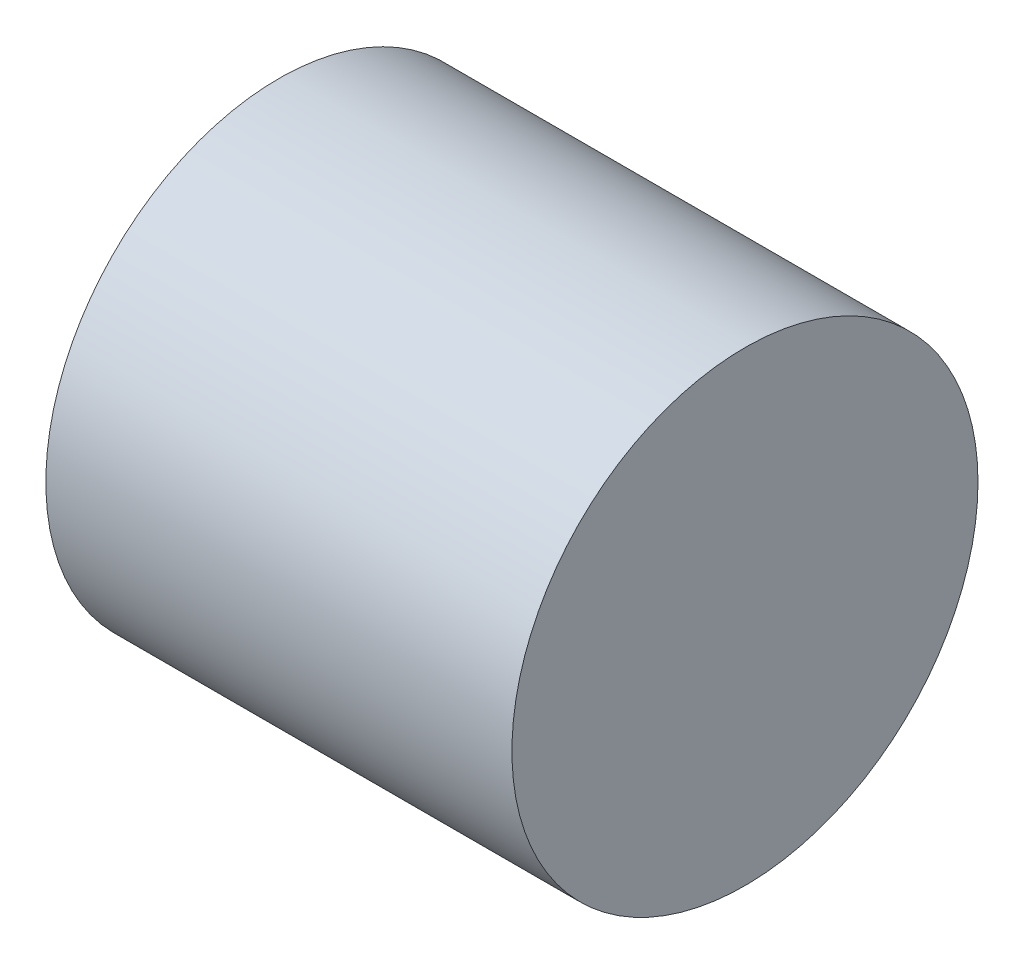
SolidWorks part; units mm, degrees
ref_plane "Front Plane" through (0, 0, 0) normal (0, 0, 1) x (1, 0, 0)
ref_plane "Top Plane" through (0, 0, 0) normal (0, 1, 0) x (1, 0, 0)
ref_plane "Right Plane" through (0, 0, 0) normal (1, 0, 0) x (0, 0, -1)
sketch "Sketch1" plane through (0, 0, 0) normal (1, 0, 0) x (0, 0, -1)
  circle A0 centre (0, 0) radius 7.5
extrude "Boss-Extrude1" add sketch "Sketch1" along normal blind 15
